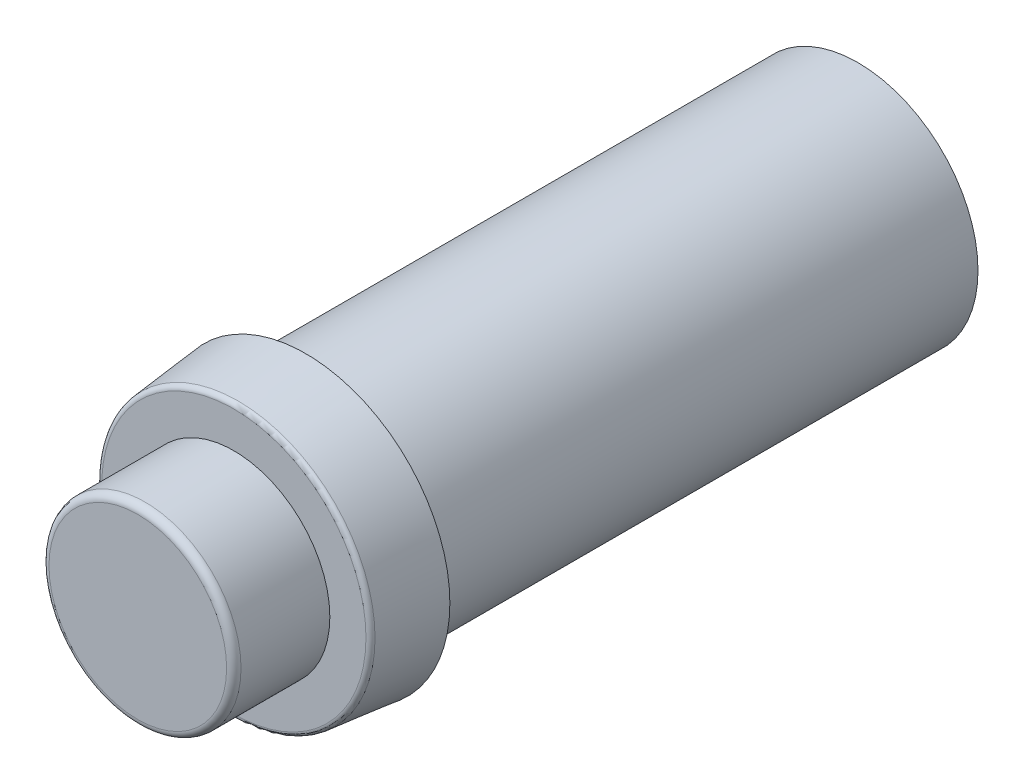
SolidWorks part; units mm, degrees
material "ABS"
ref_plane "Plano frontal" through (0, 0, 0) normal (0, 0, 1) x (1, 0, 0)
ref_plane "Plano superior" through (0, 0, 0) normal (0, 1, 0) x (1, 0, 0)
ref_plane "Plano direito" through (0, 0, 0) normal (1, 0, 0) x (0, 0, -1)
sketch "Esboço1" plane through (0, 0, 0) normal (0, 0, 1) x (1, 0, 0)
  circle A0 centre (0, 0) radius 5
  dimension "D1" = 10
extrude "Ressalto-extrusão1" add sketch "Esboço1" against normal blind 23
sketch "Esboço2" plane through (0, 0, 0) normal (0, 0, 1) x (1, 0, 0)
  circle A0 centre (0, 0) radius 6
extrude "Ressalto-extrusão2" add sketch "Esboço2" along normal blind 3 draft 6
fillet "Filete1" radius 0.2 1 edges at (5.6847, 0, 3)
sketch "Esboço3" plane through (0, 0, 3) normal (0, 0, 1) x (1, 0, 0)
  circle A0 centre (0, 0) radius 4
extrude "Ressalto-extrusão3" add sketch "Esboço3" along normal blind 4 separate body
fillet "Filete2" radius 0.3 1 edges at (4, 0, 7)
